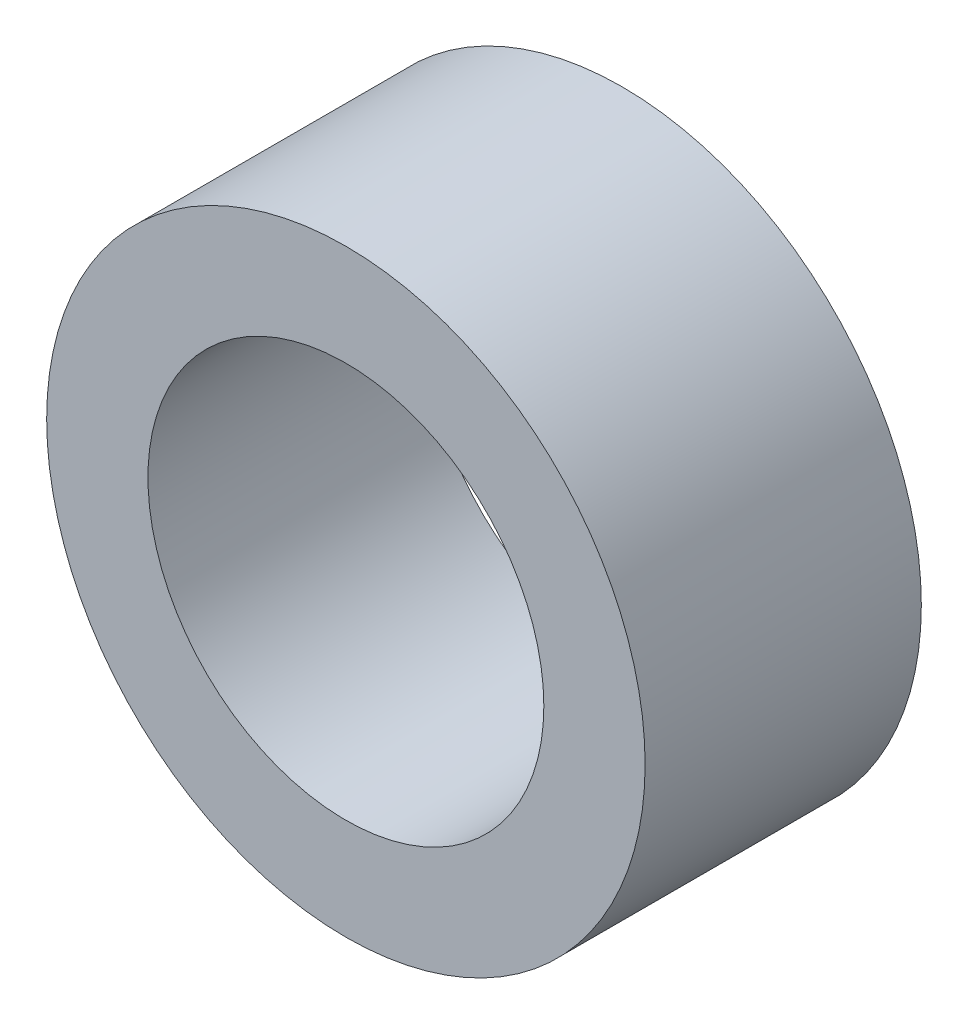
SolidWorks part; units mm, degrees
material "PLA"
ref_plane "前视基准面" through (0, 0, 0) normal (0, 0, 1) x (1, 0, 0)
ref_plane "上视基准面" through (0, 0, 0) normal (0, 1, 0) x (1, 0, 0)
ref_plane "右视基准面" through (0, 0, 0) normal (1, 0, 0) x (0, 0, -1)
other "Configuration Table"
sketch "草图1" plane through (0, 0, 0) normal (0, 0, 1) x (1, 0, 0)
  circle A0 centre (0, 0) radius 2.15
  circle A1 centre (0, 0) radius 3.25
  dimension "D1" = 6.5
  dimension "D2" = 4.3
extrude "凸台-拉伸1" add sketch "草图1" along normal blind 3
